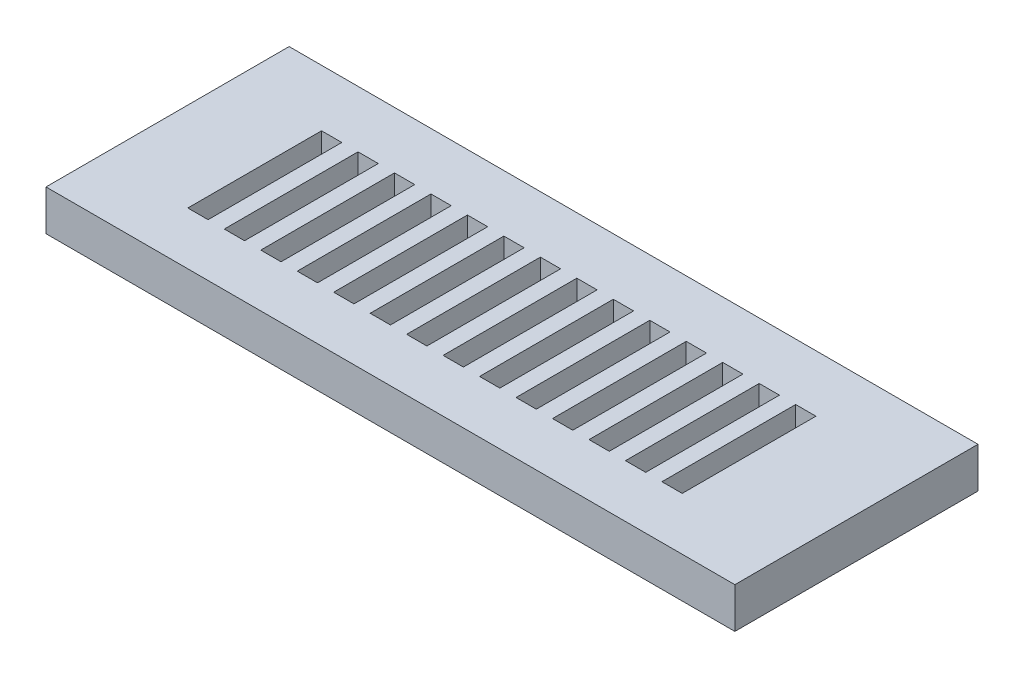
SolidWorks part; units mm, degrees
ref_plane "Front" through (0, 0, 0) normal (0, 0, 1) x (1, 0, 0)
ref_plane "Top" through (0, 0, 0) normal (0, 1, 0) x (1, 0, 0)
ref_plane "Right" through (0, 0, 0) normal (1, 0, 0) x (0, 0, -1)
sketch "Sketch1" plane through (0, 0, 0) normal (0, 1, 0) x (1, 0, 0)
  line L1 (0, 0) -> (85, 0)
  line L2 (0, 0) -> (0, 30)
  line L3 (0, 30) -> (85, 30)
  line L4 (85, 0) -> (85, 30)
  dimension "D1" = 30
  dimension "D2" = 85
extrude "Boss-Extrude1" add sketch "Sketch1" along normal blind 5
sketch "Sketch2" plane through (0, 5, 0) normal (0, 1, 0) x (1, 0, 0)
  line L0 (85, 30) -> (0, 30) construction
  line L1 (11, 23) -> (13.5, 23)
  line L2 (11, 23) -> (11, 6.5)
  line L3 (11, 6.5) -> (13.5, 6.5)
  line L4 (13.5, 23) -> (13.5, 6.5)
  line L57 (0, 30) -> (0, 0) construction
  line L58 (18, 23) -> (18, 6.5)
  line L59 (15.5, 23) -> (18, 23)
  line L60 (15.5, 23) -> (15.5, 6.5)
  line L61 (15.5, 6.5) -> (18, 6.5)
  line L62 (22.5, 23) -> (22.5, 6.5)
  line L63 (20, 23) -> (22.5, 23)
  line L64 (20, 23) -> (20, 6.5)
  line L65 (20, 6.5) -> (22.5, 6.5)
  line L66 (27, 23) -> (27, 6.5)
  line L67 (24.5, 23) -> (27, 23)
  line L68 (24.5, 23) -> (24.5, 6.5)
  line L69 (24.5, 6.5) -> (27, 6.5)
  line L70 (31.5, 23) -> (31.5, 6.5)
  line L71 (29, 23) -> (31.5, 23)
  line L72 (29, 23) -> (29, 6.5)
  line L73 (29, 6.5) -> (31.5, 6.5)
  line L74 (36, 23) -> (36, 6.5)
  line L75 (33.5, 23) -> (36, 23)
  line L76 (33.5, 23) -> (33.5, 6.5)
  line L77 (33.5, 6.5) -> (36, 6.5)
  line L78 (40.5, 23) -> (40.5, 6.5)
  line L79 (38, 23) -> (40.5, 23)
  line L80 (38, 23) -> (38, 6.5)
  line L81 (38, 6.5) -> (40.5, 6.5)
  line L82 (45, 23) -> (45, 6.5)
  line L83 (42.5, 23) -> (45, 23)
  line L84 (42.5, 23) -> (42.5, 6.5)
  line L85 (42.5, 6.5) -> (45, 6.5)
  line L86 (49.5, 23) -> (49.5, 6.5)
  line L87 (47, 23) -> (49.5, 23)
  line L88 (47, 23) -> (47, 6.5)
  line L89 (47, 6.5) -> (49.5, 6.5)
  line L90 (54, 23) -> (54, 6.5)
  line L91 (51.5, 23) -> (54, 23)
  line L92 (51.5, 23) -> (51.5, 6.5)
  line L93 (51.5, 6.5) -> (54, 6.5)
  line L94 (58.5, 23) -> (58.5, 6.5)
  line L95 (56, 23) -> (58.5, 23)
  line L96 (56, 23) -> (56, 6.5)
  line L97 (56, 6.5) -> (58.5, 6.5)
  line L98 (63, 23) -> (63, 6.5)
  line L99 (60.5, 23) -> (63, 23)
  line L100 (60.5, 23) -> (60.5, 6.5)
  line L101 (60.5, 6.5) -> (63, 6.5)
  line L102 (67.5, 23) -> (67.5, 6.5)
  line L103 (65, 23) -> (67.5, 23)
  line L104 (65, 23) -> (65, 6.5)
  line L105 (65, 6.5) -> (67.5, 6.5)
  line L106 (72, 23) -> (72, 6.5)
  line L107 (69.5, 23) -> (72, 23)
  line L108 (69.5, 23) -> (69.5, 6.5)
  line L109 (69.5, 6.5) -> (72, 6.5)
  dimension "D1" = 2.5
  dimension "D2" = 16.5
  dimension "D3" = 7
  dimension "D5" = 11
extrude "Cut-Extrude1" cut sketch "Sketch2" against normal blind 5
